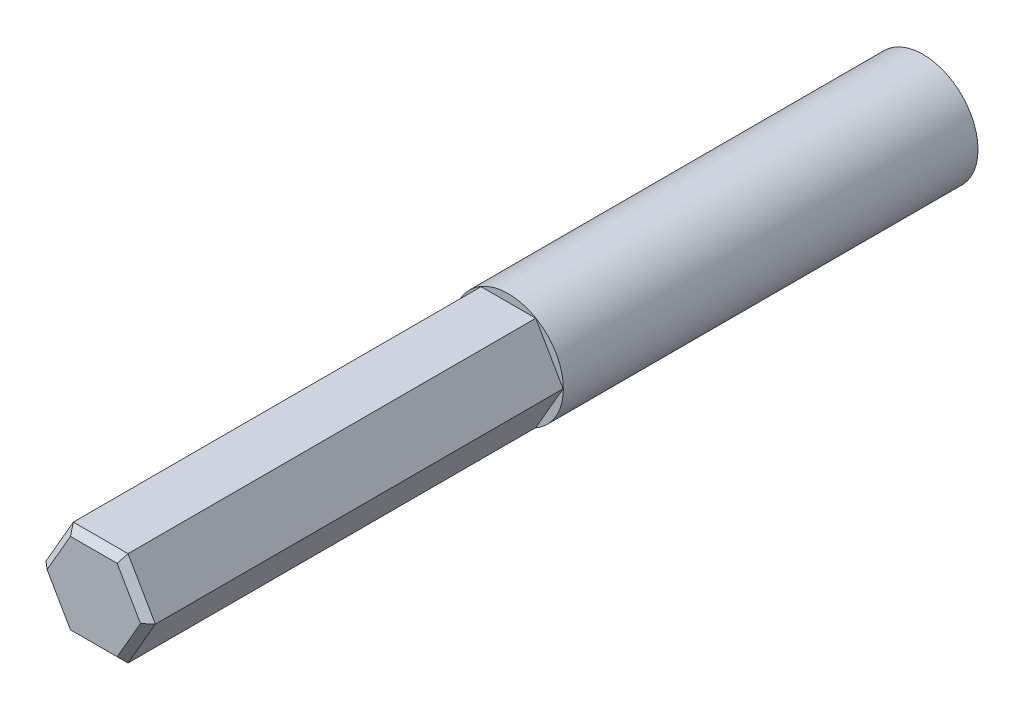
SolidWorks part; units mm, degrees
material "PETG"
ref_plane "Front Plane" through (0, 0, 0) normal (0, 0, 1) x (1, 0, 0)
ref_plane "Top Plane" through (0, 0, 0) normal (0, 1, 0) x (1, 0, 0)
ref_plane "Right Plane" through (0, 0, 0) normal (1, 0, 0) x (0, 0, -1)
sketch "Sketch1" plane through (0, 0, 0) normal (0, 0, 1) x (1, 0, 0)
  circle A0 centre (0, 0) radius 3.975
  dimension "Shaft Dia" = 7.95
extrude "Boss-Extrude1" add sketch "Sketch1" along normal blind 30
sketch "Sketch2" plane through (0, 0, 30) normal (0, 0, 1) x (1, 0, 0)
  line L1 (4, 0) -> (2, 3.4641) construction
  line L2 (2, 3.4641) -> (-2, 3.4641) construction
  line L3 (-2, 3.4641) -> (-4, 0) construction
  line L4 (-4, 0) -> (-2, -3.4641) construction
  line L5 (-2, -3.4641) -> (2, -3.4641) construction
  line L6 (2, -3.4641) -> (4, 0) construction
  line L7 (3.9567, 0) -> (1.9783, 3.4266)
  line L8 (1.9783, 3.4266) -> (-1.9783, 3.4266)
  line L9 (-1.9783, 3.4266) -> (-3.9567, 0)
  line L10 (-3.9567, 0) -> (-1.9783, -3.4266)
  line L11 (-1.9783, -3.4266) -> (1.9783, -3.4266)
  line L12 (1.9783, -3.4266) -> (3.9567, 0)
  circle A0 centre (0, 0) radius 3.4641 construction
  circle A1 centre (0, 0) radius 3.4266 construction
  dimension "Hex Circumscribed Nominal Dia" = 8
  dimension "Hex Flat To Flat Offset" = 0.0375
extrude "Boss-Extrude2" add sketch "Sketch2" along normal blind 30
chamfer "Chamfer2" distance 0.5 angle 45 6 edges at (0, -3.4266, 60) (-2.9675, -1.7133, 60) (-2.9675, 1.7133, 60) (0, 3.4266, 60) (2.9675, 1.7133, 60) (2.9675, -1.7133, 60)
equation "\"tol_dia_id_intfc\" = 0.0500mm ' For hole diameters - Interference fit"
equation "\"tol_dia_id_slip\"  = 0.0750mm ' For hole diameters - Slip fit"
equation "\"tol_dia_id_clear\" = 0.1000mm ' For hole diameters - Clearance fit"
equation "\"tol_dia_od_intfc\" = 0.0500mm ' For shaft diameters - Interference fit"
equation "\"tol_dia_od_slip\"  = 0.0750mm ' For shaft diameters - Slip fit"
equation "\"tol_dia_od_clear\" = 0.1000mm ' For shaft diameters - Clearance fit"
equation "\"tol_general_intfc\"= 0.0250mm ' For general parts (Horiz) - Interference fit"
equation "\"tol_general_slip\" = 0.0375mm ' For general parts (Horiz) - Slip fit"
equation "\"tol_general_clear\"= 0.0500mm ' For general parts (Horiz) - Clearance fit"
equation "\"tol_layer_intfc\"  = 0.0250mm ' For all parts (Vert) - Interference fit"
equation "\"tol_layer_slip\"   = 0.0375mm ' For all parts (Vert) - Slip fit"
equation "\"tol_layer_clear\"  = 0.0500mm ' For all parts (Vert) - Clearance fit"
equation "\"tol_corner_rad\"   = 0.100mm ' For corners that fit into other parts"
equation "\"Shaft Dia@Sketch1\" = \"nominal_dia\" - \"tol_dia_od_intfc\""
equation "\"nominal_dia\"= 8.00mm"
equation "\"Hex Circumscribed Nominal Dia@Sketch2\" = \"nominal_dia\""
equation "\"Hex Flat To Flat Offset@Sketch2\"=\"tol_general_slip\""
equation "\"D1@Fillet1\"=\"tol_corner_rad\""
